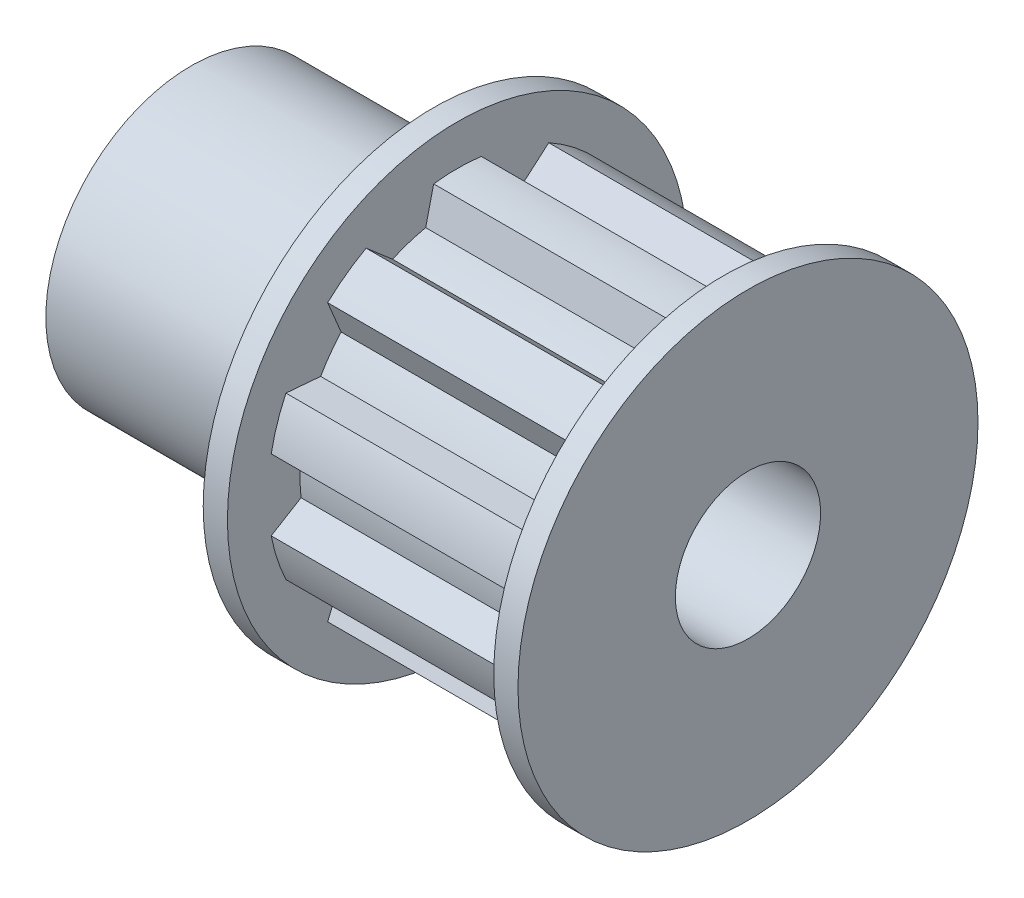
SolidWorks part; units mm, degrees
material "AISI 304"
ref_plane "前视基准面" through (0, 0, 0) normal (0, 0, 1) x (1, 0, 0)
ref_plane "上视基准面" through (0, 0, 0) normal (0, 1, 0) x (1, 0, 0)
ref_plane "右视基准面" through (0, 0, 0) normal (1, 0, 0) x (0, 0, -1)
sketch "Sketch1" plane through (0, 0, 0) normal (1, 0, 0) x (0, 0, -1)
  circle A0 centre (0, 0) radius 6
  dimension "D1" = 12
extrude "Boss-Extrude1" add sketch "Sketch1" along normal blind 10
sketch "Sketch2" plane through (10, 0, 0) normal (1, 0, 0) x (0, 0, -1)
  circle A0 centre (0, 0) radius 9.5
  dimension "D1" = 19
extrude "Boss-Extrude2" add sketch "Sketch2" along normal blind 1
sketch "Sketch3" plane through (11, 0, 0) normal (1, 0, 0) x (0, 0, -1)
  line L0 (0, 10.7415) -> (0, -11.8442) construction
  line L1 (-15.3373, 0) -> (14.9401, 0) construction
  line L2 (-0.9825, 7.7681) -> (-1.3117, 6.3663)
  line L3 (0.9825, 7.7681) -> (1.3117, 6.3663)
  line L4 (3.7712, 6.862) -> (2.6808, 5.9214)
  line L5 (5.3608, 5.7071) -> (4.8032, 4.3794)
  line L6 (7.0843, 3.3349) -> (5.6493, 3.2148)
  line L7 (7.6915, 1.4661) -> (6.46, 0.7198)
  line L8 (7.6915, -1.4661) -> (6.46, -0.7198)
  line L9 (7.0843, -3.3349) -> (5.6493, -3.2148)
  line L10 (5.3608, -5.7071) -> (4.8032, -4.3794)
  line L11 (3.7712, -6.862) -> (2.6808, -5.9214)
  line L12 (0.9825, -7.7681) -> (1.3117, -6.3663)
  line L13 (-0.9825, -7.7681) -> (-1.3117, -6.3663)
  line L14 (-3.7712, -6.862) -> (-2.6808, -5.9214)
  line L15 (-5.3608, -5.7071) -> (-4.8032, -4.3794)
  line L16 (-7.0843, -3.3349) -> (-5.6493, -3.2148)
  line L17 (-7.6915, -1.4661) -> (-6.46, -0.7198)
  line L18 (-7.6915, 1.4661) -> (-6.46, 0.7198)
  line L19 (-7.0843, 3.3349) -> (-5.6493, 3.2148)
  line L20 (-5.3608, 5.7071) -> (-4.8032, 4.3794)
  line L21 (-3.7712, 6.862) -> (-2.6808, 5.9214)
  arc A0 (-3.7712, 6.862) -> (-5.3608, 5.7071) centre (0, 0) ccw
  arc A1 (-1.3117, 6.3663) -> (-2.6808, 5.9214) centre (0, 0) ccw
  arc A2 (0.9825, 7.7681) -> (-0.9825, 7.7681) centre (0, 0) ccw
  arc A3 (2.6808, 5.9214) -> (1.3117, 6.3663) centre (0, 0) ccw
  arc A4 (5.3608, 5.7071) -> (3.7712, 6.862) centre (0, 0) ccw
  arc A5 (7.6915, 1.4661) -> (7.0843, 3.3349) centre (0, 0) ccw
  arc A6 (5.6493, 3.2148) -> (4.8032, 4.3794) centre (0, 0) ccw
  arc A7 (6.46, -0.7198) -> (6.46, 0.7198) centre (0, 0) ccw
  arc A8 (4.8032, -4.3794) -> (5.6493, -3.2148) centre (0, 0) ccw
  arc A9 (1.3117, -6.3663) -> (2.6808, -5.9214) centre (0, 0) ccw
  arc A10 (-2.6808, -5.9214) -> (-1.3117, -6.3663) centre (0, 0) ccw
  arc A11 (-5.6493, -3.2148) -> (-4.8032, -4.3794) centre (0, 0) ccw
  arc A12 (-6.46, 0.7198) -> (-6.46, -0.7198) centre (0, 0) ccw
  arc A13 (-4.8032, 4.3794) -> (-5.6493, 3.2148) centre (0, 0) ccw
  arc A14 (-7.0843, 3.3349) -> (-7.6915, 1.4661) centre (0, 0) ccw
  arc A15 (-7.6915, -1.4661) -> (-7.0843, -3.3349) centre (0, 0) ccw
  arc A16 (-5.3608, -5.7071) -> (-3.7712, -6.862) centre (0, 0) ccw
  arc A17 (-0.9825, -7.7681) -> (0.9825, -7.7681) centre (0, 0) ccw
  arc A18 (3.7712, -6.862) -> (5.3608, -5.7071) centre (0, 0) ccw
  arc A19 (7.0843, -3.3349) -> (7.6915, -1.4661) centre (0, 0) ccw
  point P51 (0, 0)
  dimension "D1" = 15.66
  dimension "D2" = 13
  dimension "D4" = 1.44
  dimension "D5" = 0.9825
  dimension "D3" = 10
extrude "Boss-Extrude3" add sketch "Sketch3" along normal blind 11
sketch "Sketch4" plane through (22, 0, 0) normal (1, 0, 0) x (0, 0, -1)
  circle A0 centre (0, 0) radius 9.5
  dimension "D1" = 19
extrude "Boss-Extrude4" add sketch "Sketch4" along normal blind 1
sketch "Sketch5" plane through (0, 0, 0) normal (-1, 0, 0) x (0, 0, 1)
  circle A0 centre (0, 0) radius 3
  dimension "D1" = 6
extrude "Cut-Extrude1" cut sketch "Sketch5" against normal through all
sketch "Sketch6" plane through (0, 0, 0) normal (0, 1, 0) x (1, 0, 0)
  line L0 (-2.0703, 0) -> (24.008, 0) construction
  line L1 (5, -7.1707) -> (5, 8.3529) construction
  line L2 (0, 6) -> (0, -6) construction
  circle A0 centre (5, 0) radius 2
  dimension "D2" = 4
  dimension "D1" = 5
extrude "Cut-Extrude2" cut sketch "Sketch6" against normal through all
